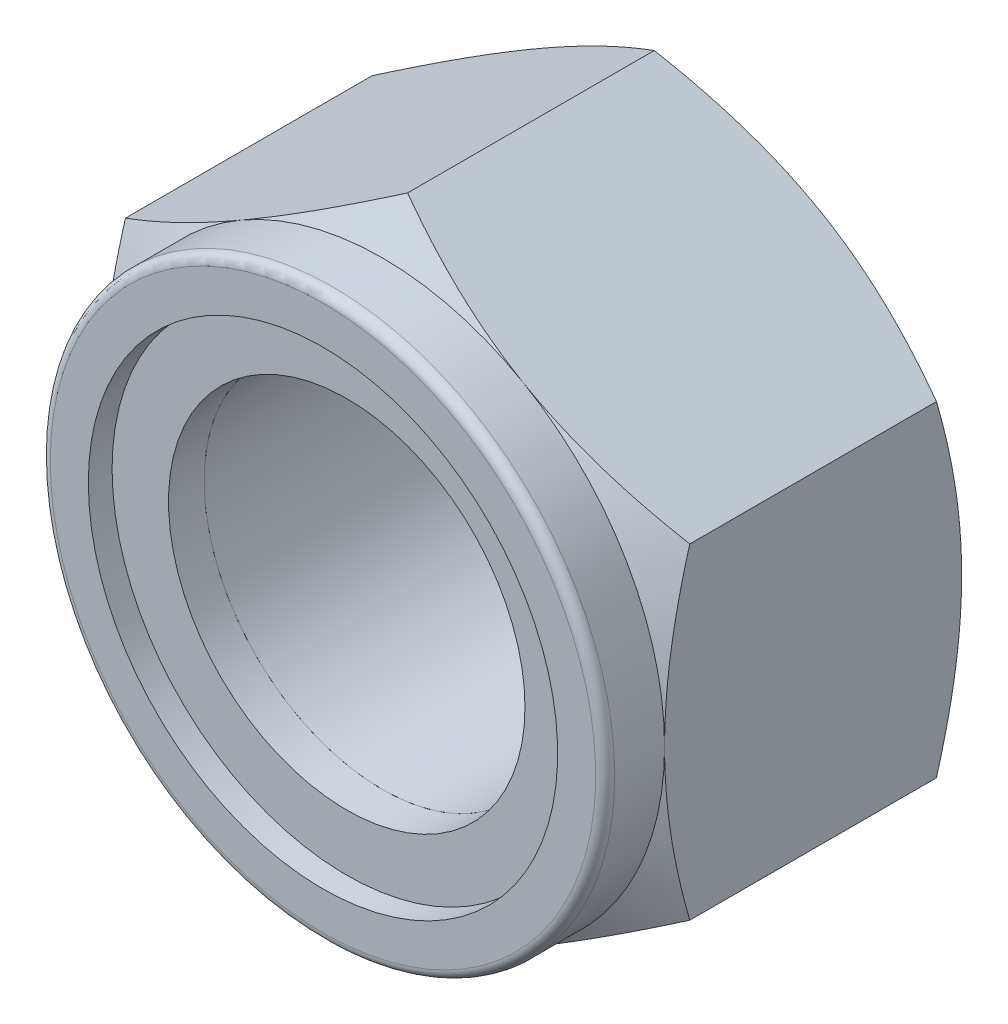
SolidWorks part; units mm, degrees
material "Stainless Steel (ferritic)"
ref_plane "Front" through (0, 0, 0) normal (0, 0, 1) x (1, 0, 0)
ref_plane "Top" through (0, 0, 0) normal (0, 1, 0) x (1, 0, 0)
ref_plane "Right" through (0, 0, 0) normal (1, 0, 0) x (0, 0, -1)
sketch "Sketch1" plane through (0, 0, 0) normal (0, 0, 1) x (1, 0, 0)
  line L1 (0, 10.9697) -> (-9.5, 5.4848)
  line L2 (-9.5, 5.4848) -> (-9.5, -5.4848)
  line L3 (-9.5, -5.4848) -> (0, -10.9697)
  line L4 (0, -10.9697) -> (9.5, -5.4848)
  line L5 (9.5, -5.4848) -> (9.5, 5.4848)
  line L6 (9.5, 5.4848) -> (0, 10.9697)
  circle A0 centre (0, 0) radius 9.5 construction
  dimension "S" = 19
extrude "Extrude1" add sketch "Sketch1" along normal blind 10
sketch "Sketch2" plane through (0, 0, 0) normal (0, 1, 0) x (1, 0, 0)
  line L0 (9.5, -10) -> (13.3, -10)
  line L1 (13.3, -10) -> (13.3, -7.8061)
  line L2 (13.3, -7.8061) -> (9.5, -10)
  line L3 (0, 0) -> (0, -10) construction
  dimension "D1" = 30
  dimension "D2" = 3.8
revolve "Cut-Revolve1" cut sketch "Sketch2" angle 360 about L3
ref_plane "Plane1" through (0, 0, 5) normal (0, 0, -1) x (-1, 0, 0)
mirror "Mirror1" about plane through (0, 0, 5) normal (0, 0, -1) of "Cut-Revolve1"
sketch "Sketch3" plane through (0, 0, 0) normal (0, 1, 0) x (1, 0, 0)
  line L0 (9.5, -10) -> (9.5, -12)
  line L1 (9.5, -12) -> (7.9, -12)
  line L2 (7.9, -12) -> (7.9, -11.2)
  line L3 (7.9, -11.2) -> (8.7, -11.2)
  line L4 (8.7, -10) -> (8.7, -11.2)
  line L5 (4.75, -10) -> (9.5, -10) construction
  line L6 (9.5, 0) -> (0, 0) construction
  line L7 (9.5, -10) -> (8.7, -10)
  line L8 (0, 0) -> (0, -10) construction
  line L9 (-4.75, -10) -> (4.75, -10) construction
  line L10 (4.75, 0) -> (-4.75, 0) construction
  dimension "m" = 12
  dimension "D1" = 0.8
  dimension "D2" = 1.6
revolve "Revolve1" add sketch "Sketch3" angle 360 about L8
sketch "Sketch4" plane through (0, 0, 0) normal (0, 0, -1) x (-1, 0, 0)
  circle A0 centre (0, 0) radius 6
  dimension "d" = 12
sketch "Sketch5" plane through (0, 0, 10) normal (0, 0, 1) x (1, 0, 0)
  circle A0 centre (0, 0) radius 8.7
  circle A1 centre (0, 0) radius 6
  circle A2 centre (0, 0) radius 8.7 construction
  dimension "D1" = 12
extrude "Extrude2" add sketch "Sketch5" along normal up to surface (1.2 mm away) separate body up to face at (-7.9, 0, 11.2)
extrude "Cut-Extrude1" cut sketch "Sketch4" against normal through all
fillet "Fillet2" radius 0.32 1 edges at (-9.5, 0, 12)
equation "\"D2@Sketch2\" = \"S@Sketch1\" / 5"
equation "\"D1@Sketch3\" = \"m@Sketch3\" / 15"
equation "\"D2@Sketch3\" = \"D1@Sketch3\" * 2"
equation "\"D1@Sketch5\" = \"d@Sketch4\""
equation "\"D1@Fillet2\" = \"D2@Sketch3\" / 5"
equation "\"D1@Plane1\" = \"m2@Extrude1\" / 2"
